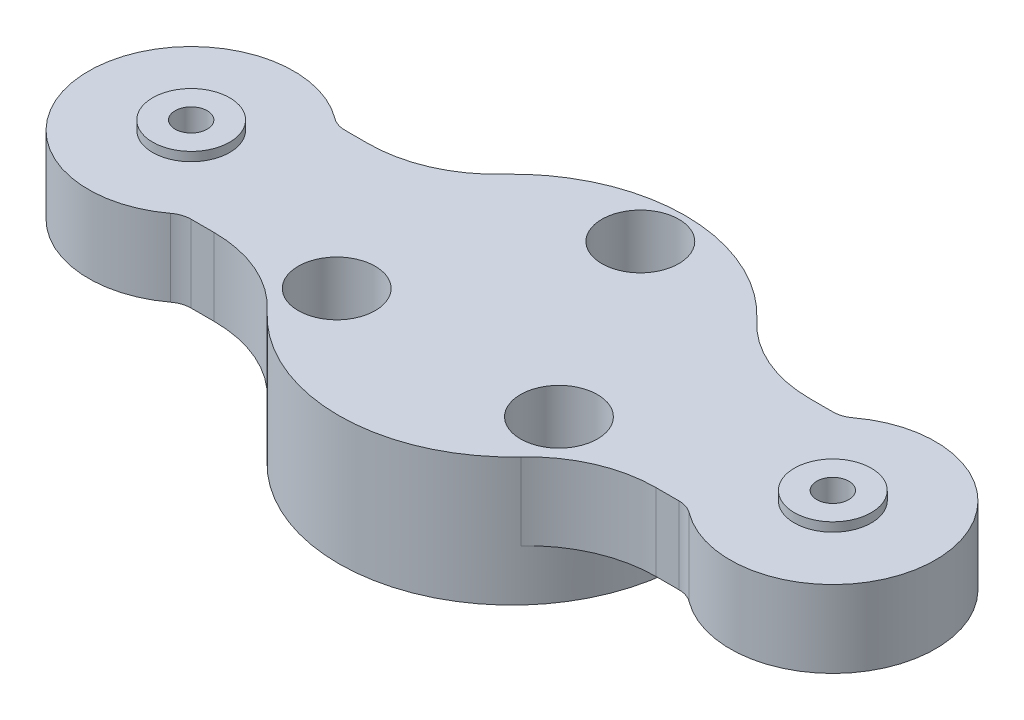
SolidWorks part; units mm, degrees
material "6061 合金"
ref_plane "Front Plane" through (0, 0, 0) normal (0, 0, 1) x (1, 0, 0)
ref_plane "Top Plane" through (0, 0, 0) normal (0, 1, 0) x (1, 0, 0)
ref_plane "Right Plane" through (0, 0, 0) normal (1, 0, 0) x (0, 0, -1)
other "Configuration Table"
sketch "草图1" plane through (0, 0, 0) normal (0, 1, 0) x (1, 0, 0)
  line L1 (0, 10) -> (-8.6603, -5) construction
  line L2 (-8.6603, -5) -> (8.6603, -5) construction
  line L3 (8.6603, -5) -> (0, 10) construction
  circle A0 centre (0, 0) radius 13.5
  circle A1 centre (0, 0) radius 10 construction
  circle A2 centre (0, 10) radius 1.6
  circle A3 centre (8.6603, -5) radius 1.6
  circle A4 centre (-8.6603, -5) radius 1.6
  point P15 (0, 0)
  dimension "D1" = 27
  dimension "D2" = 20
  dimension "D3" = 3.2
  dimension "D4" = 3
extrude "凸台-拉伸1" add sketch "草图1" along normal blind 10
sketch "草图2" plane through (0, 10, 0) normal (0, 1, 0) x (1, 0, 0)
  line L0 (-25, 0) -> (25, 0) construction
  line L1 (0, 13.5) -> (0, -13.5) construction
  line L2 (-19.7085, 6) -> (-12.0934, 6)
  line L3 (-19.7085, -6) -> (-12.0934, -6)
  line L4 (19.7085, -6) -> (12.0934, -6)
  line L5 (19.7085, 6) -> (12.0934, 6)
  arc A0 (-19.7085, 6) -> (-19.7085, -6) centre (-25, 0) ccw
  circle A1 centre (-25, 0) radius 1
  circle A2 centre (0, 0) radius 13.5 construction
  arc A3 (-12.0934, 6) -> (-12.0934, -6) centre (0, 0) ccw
  arc A4 (12.0934, -6) -> (0, 13.5) centre (0, 0) ccw
  arc A5 (12.0934, 6) -> (12.0934, -6) centre (0, 0) cw
  circle A6 centre (25, 0) radius 1
  arc A7 (19.7085, 6) -> (19.7085, -6) centre (25, 0) cw
  point P3 (0, 0)
  circle M7 centre (0, 0) radius 13.5
  dimension "D2" = 16
  dimension "D3" = 2
  dimension "D1" = 25
  dimension "D4" = 6
extrude "凸台-拉伸2" add sketch "草图2" against normal blind 6 contours L2 A0 L3 A1 M7 | A7 L5 L4 A6 M7
sketch "草图3" plane through (0, 10, 0) normal (0, 1, 0) x (1, 0, 0)
  circle A0 centre (0, 10) radius 3
  circle A1 centre (8.6603, -5) radius 3
  circle A2 centre (-8.6603, -5) radius 3
  dimension "D1" = 6
  dimension "D2" = 6
  dimension "D3" = 6
extrude "切除-拉伸1" cut sketch "草图3" against normal offset from surface (5 mm away) 5 up to face at (0, 0, 13.5)
sketch "草图4" plane through (0, 10, 0) normal (0, 1, 0) x (1, 0, 0)
  circle A0 centre (25, 0) radius 1 construction
  circle A1 centre (-25, 0) radius 1 construction
  circle A2 centre (25, 0) radius 1
  circle A3 centre (-25, 0) radius 1
  circle A4 centre (-25, 0) radius 3
  circle A5 centre (25, 0) radius 3
  dimension "D1" = 6
  dimension "D2" = 6
extrude "凸台-拉伸3" add sketch "草图4" along normal blind 0.7
fillet "圆角1" radius 10 4 edges at (12.0934, 7, 6) (12.0934, 7, -6) (-12.0934, 7, -6) (-12.0934, 7, 6)
fillet "圆角2" radius 2 4 edges at (19.7085, 7, -6) (19.7085, 7, 6) (-19.7085, 7, -6) (-19.7085, 7, 6)
hole_wizard "M3 螺纹孔1" positions "草图5" profile "草图6" tap size "M3" standard "GB" end condition through all
sketch "草图5" plane through (0, 10.7, 0) normal (0, 1, 0) x (1, 0, 0)
  point P0 (-25, 0)
  point P3 (25, 0)
sketch "草图6" plane through (-25, 10.7, 0) normal (1, 0, 0) x (0, 0, 1)
  line L0 (0, 0) -> (0, 10.7)
  line L1 (0, 10.7) -> (1.25, 10.7)
  line L2 (1.25, 10.7) -> (1.25, 0)
  line L5 (1.25, 0) -> (0, 0)
  line L11 (0, -6.35) -> (0, 107.95) construction
  dimension "通孔螺纹孔钻头直径" = 2.5
  dimension "通孔螺纹孔钻头深度" = 10.7
sketch "草图7" plane through (0, 0, 0) normal (0, -1, 0) x (1, 0, 0)
  line L0 (0, 10) -> (0, 0) construction
  line L1 (0, 0) -> (-8.6603, 5) construction
  line L2 (0, 0) -> (-8.6603, -5) construction
  circle A0 centre (0, 0) radius 10 construction
  circle A1 centre (0, 10) radius 1
  circle A2 centre (8.6603, -5) radius 1
  circle A3 centre (-8.6603, -5) radius 1
  point P3 (0, 10)
  point P10 (8.6603, -5)
  point P12 (-8.6603, -5)
  dimension "D1" = 20
  dimension "D2" = 2
  dimension "D3" = 60
  dimension "D5" = 60
  dimension "D4" = 3
hole_wizard "Ø2.0mm 暗销孔2" positions "草图7" profile "草图11" hole size "Ø2.0" standard "GB"
sketch "草图11" plane through (-8.6603, 0, -5) normal (1, 0, 0) x (0, 0, -1)
  line L0 (0, 0) -> (0, 6.6009)
  line L1 (0, 6.6009) -> (1, 6)
  line L2 (1, 6) -> (1, 0)
  line L5 (1, 0) -> (0, 0)
  line L10 (0, 6.6009) -> (-1, 6) construction
  line L11 (0, -6.35) -> (0, 107.95) construction
  dimension "孔直径" = 2
  dimension "孔深度" = 6
  dimension "导头角度" = 118
